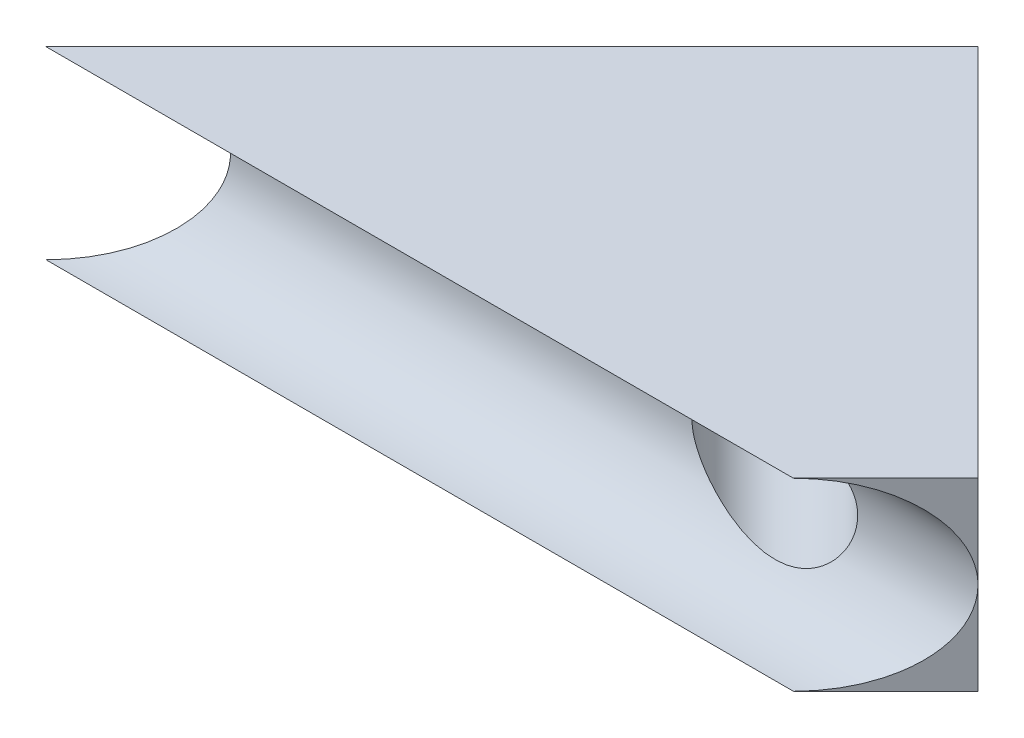
SolidWorks part; units mm, degrees
ref_plane "Front Plane" through (0, 0, 0) normal (0, 0, 1) x (1, 0, 0)
ref_plane "Top Plane" through (0, 0, 0) normal (0, 1, 0) x (1, 0, 0)
ref_plane "Right Plane" through (0, 0, 0) normal (1, 0, 0) x (0, 0, -1)
sketch "Sketch1" plane through (0, 0, 0) normal (0, 1, 0) x (1, 0, 0)
  line L0 (0, 0) -> (353.5534, 0)
  line L1 (0, 0) -> (176.7767, 176.7767)
  line L2 (176.7767, 176.7767) -> (353.5534, 0)
  dimension "D1" = 90
  dimension "D2" = 45
  dimension "D3" = 250
extrude "Boss-Extrude1" add sketch "Sketch1" along normal blind 70
sketch "Sketch3" plane through (0, 0, 0) normal (1, 0, 0) x (0, 0, -1)
  line L0 (0, 70) -> (0, 0) construction
  line L1 (0, 70) -> (0, 0)
  arc A0 (0, 0) -> (0, 70) centre (0, 35) ccw
extrude "Cut-Extrude1" cut sketch "Sketch3" along normal blind 402
sketch "Sketch4" plane through (0, 0, 0) normal (0, -1, 0) x (1, 0, 0)
  line L0 (318.5534, -35) -> (283.5534, 0)
  line L1 (0, 0) -> (353.5534, 0) construction
  line L2 (283.5534, 0) -> (353.5534, 0)
  line L3 (353.5534, 0) -> (318.5534, -35)
extrude "Cut-Extrude3" cut sketch "Sketch4" against normal blind 164
sketch "Sketch5" plane through (0, 0, 0) normal (-0.7071, 0, -0.7071) x (-0.7071, 0, 0.7071)
  circle A0 centre (-195.5073, 35) radius 22.2312
extrude "Cut-Extrude4" cut sketch "Sketch5" against normal blind 251
